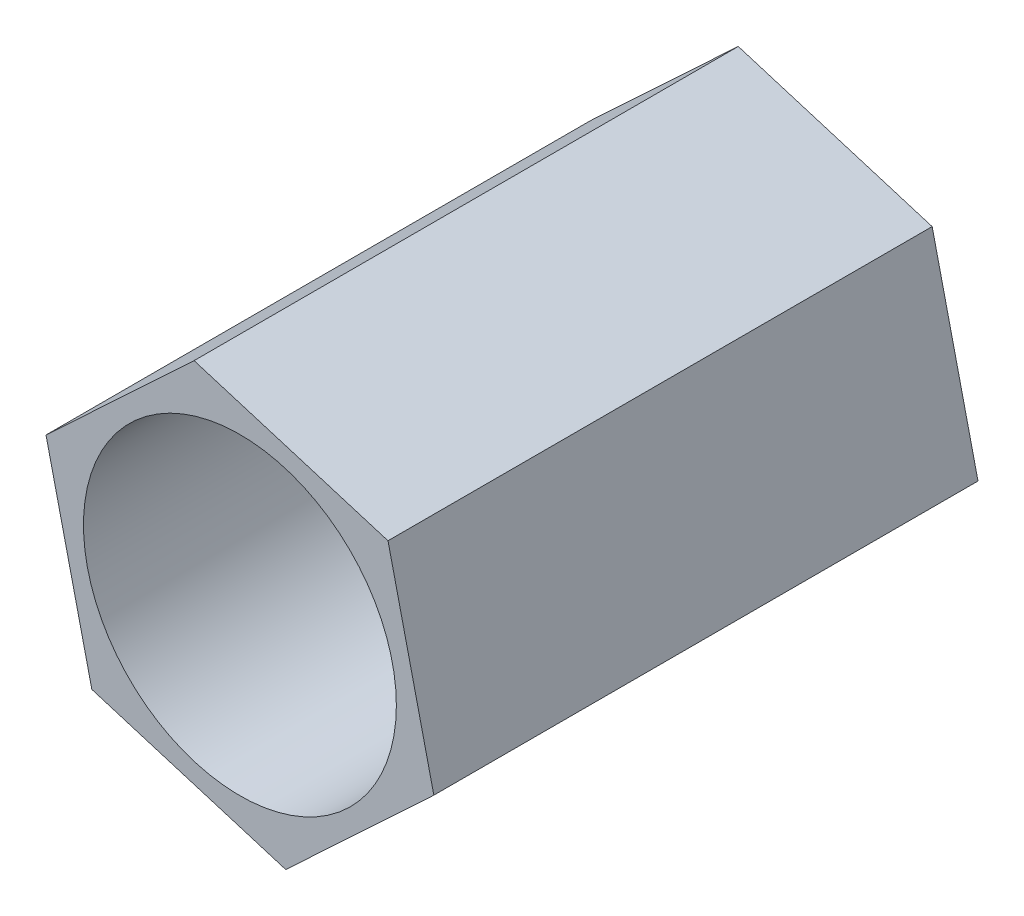
SolidWorks part; units mm, degrees
ref_plane "Front Plane" through (0, 0, 0) normal (0, 0, 1) x (1, 0, 0)
ref_plane "Top Plane" through (0, 0, 0) normal (0, 1, 0) x (1, 0, 0)
ref_plane "Right Plane" through (0, 0, 0) normal (1, 0, 0) x (0, 0, -1)
sketch "Sketch1" plane through (0, 0, 0) normal (0, 0, 1) x (1, 0, 0)
  line L1 (-2.7212, -2.5438) -> (0.8424, -3.6285)
  line L2 (0.8424, -3.6285) -> (3.5636, -1.0847)
  line L3 (3.5636, -1.0847) -> (2.7212, 2.5438)
  line L4 (2.7212, 2.5438) -> (-0.8424, 3.6285)
  line L5 (-0.8424, 3.6285) -> (-3.5636, 1.0847)
  line L6 (-3.5636, 1.0847) -> (-2.7212, -2.5438)
  circle A0 centre (0, 0) radius 2.875
  circle A1 centre (0, 0) radius 3.2259 construction
  point P3 (0, 0)
  point P11 (0, 0)
  dimension "D1" = 7.45
  dimension "D2" = 5.75
extrude "Boss-Extrude1" add sketch "Sketch1" along normal blind 10
